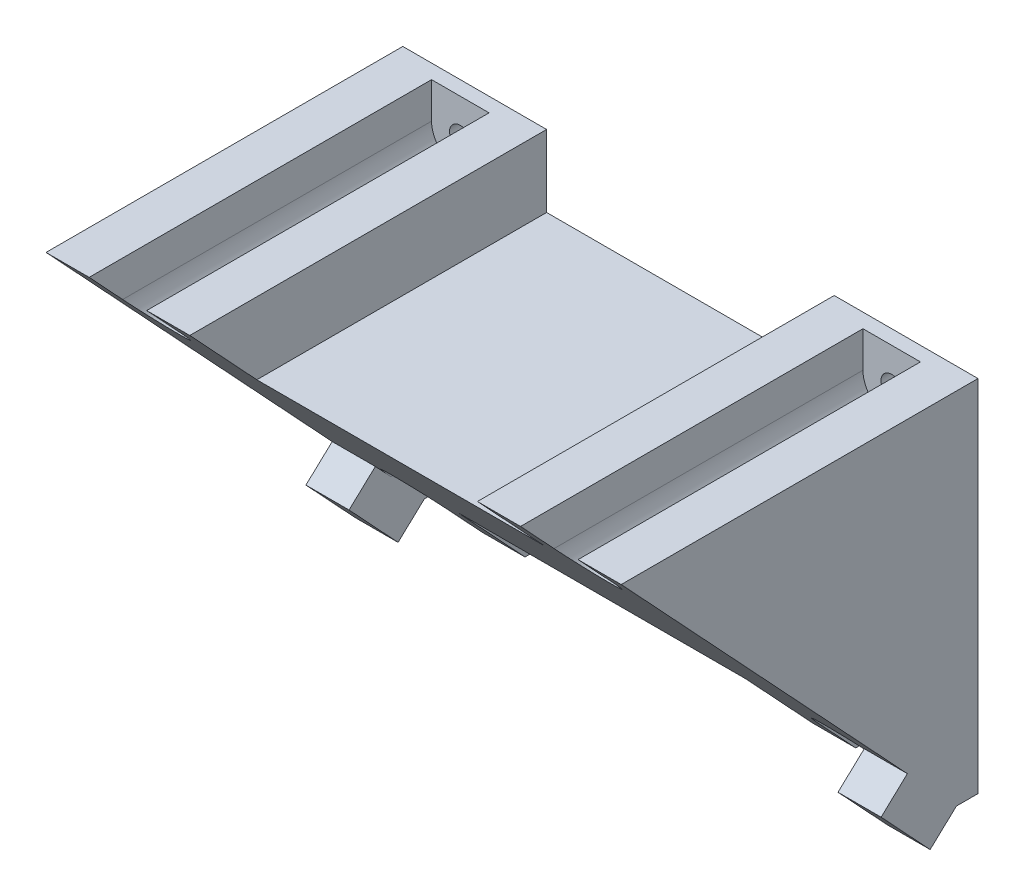
SolidWorks part; units mm, degrees
ref_plane "前视基准面" through (0, 0, 0) normal (0, 0, 1) x (1, 0, 0)
ref_plane "上视基准面" through (0, 0, 0) normal (0, 1, 0) x (1, 0, 0)
ref_plane "右视基准面" through (0, 0, 0) normal (1, 0, 0) x (0, 0, -1)
sketch "草图1" plane through (0, 0, 0) normal (0, 0, 1) x (1, 0, 0)
  line L0 (0, 0) -> (0, 50)
  line L1 (20, 50) -> (20, 40)
  line L2 (60, 40) -> (20, 40)
  line L3 (60, 50) -> (60, 40)
  line L4 (20, 50) -> (0, 50)
  line L5 (60, 50) -> (80, 50)
  line L6 (80, 50) -> (80, 0)
  line L7 (80, 0) -> (60, 0)
  line L8 (60, 0) -> (60, 10)
  line L9 (60, 10) -> (20, 10)
  line L10 (20, 10) -> (20, 0)
  line L11 (20, 0) -> (0, 0)
  point P13 (0, 0)
  point P14 (0, 0)
  dimension "D1" = 50
  dimension "D2" = 20
  dimension "D3" = 40
  dimension "D4" = 20
  dimension "D5" = 20
  dimension "D6" = 40
  dimension "D7" = 20
  dimension "D8" = 10
  dimension "D10" = 10
extrude "凸台-拉伸2" add sketch "草图1" along normal blind 2
sketch "草图3" plane through (0, 0, 2) normal (0, 0, 1) x (1, 0, 0)
  line L0 (10, 5) -> (10, 0) construction
  line L2 (20, 0) -> (0, 0) construction
  line L3 (10, 50) -> (10, 45) construction
  line L4 (20, 50) -> (0, 50) construction
  line L5 (70, 50) -> (70, 45) construction
  line L6 (60, 50) -> (80, 50) construction
  line L7 (70, 0) -> (70, 5) construction
  line L8 (80, 0) -> (60, 0) construction
  circle A1 centre (10, 45) radius 1.5
  circle A2 centre (10, 5) radius 1.5
  circle A3 centre (70, 45) radius 1.5
  circle A4 centre (70, 5) radius 1.5
  point P20 (0, 0)
  dimension "D1" = 3
  dimension "D4" = 3
  dimension "D5" = 3
  dimension "D6" = 3
  dimension "D2" = 40
  dimension "D3" = 40
  dimension "D7" = 60
  dimension "D8" = 60
  dimension "D9" = 10
  dimension "D10" = 10
  dimension "D11" = 10
  dimension "D12" = 10
extrude "切除-拉伸1" cut sketch "草图3" against normal through all
sketch "草图5" plane through (0, 0, 2) normal (0, 0, 1) x (1, 0, 0)
  line L0 (0, 50) -> (6, 50)
  line L1 (20, 50) -> (0, 50) construction
  line L2 (6, 50) -> (6, 45)
  line L3 (14, 45) -> (14, 50)
  line L4 (14, 50) -> (20, 50)
  line L5 (20, 50) -> (20, 40)
  line L6 (20, 40) -> (60, 40)
  line L7 (60, 40) -> (60, 50)
  line L8 (60, 50) -> (66, 50)
  line L9 (60, 50) -> (80, 50) construction
  line L10 (66, 50) -> (66, 45)
  line L11 (74, 45) -> (74, 50)
  line L12 (74, 50) -> (80, 50)
  line L13 (80, 50) -> (80, 0)
  line L14 (80, 0) -> (74, 0)
  line L15 (80, 0) -> (60, 0) construction
  line L16 (74, 0) -> (74, 5)
  line L17 (66, 5) -> (66, 0)
  line L18 (66, 0) -> (60, 0)
  line L19 (60, 0) -> (60, 10)
  line L20 (60, 10) -> (20, 10)
  line L21 (20, 10) -> (20, 0)
  line L22 (20, 0) -> (14, 0)
  line L23 (20, 0) -> (0, 0) construction
  line L24 (14, 0) -> (14, 5)
  line L25 (6, 5) -> (6, 0)
  line L26 (6, 0) -> (0, 0)
  line L27 (0, 0) -> (0, 50)
  arc A0 (6, 45) -> (14, 45) centre (10, 45) ccw
  arc A1 (66, 45) -> (74, 45) centre (70, 45) ccw
  arc A2 (74, 5) -> (66, 5) centre (70, 5) ccw
  arc A3 (14, 5) -> (6, 5) centre (10, 5) ccw
  dimension "D5" = 4
  dimension "D6" = 4
  dimension "D7" = 4
  dimension "D8" = 4
  dimension "D1" = 5
  dimension "D2" = 5
  dimension "D3" = 5
  dimension "D4" = 5
  dimension "D9" = 10
  dimension "D10" = 10
  dimension "D11" = 10
  dimension "D12" = 10
extrude "凸台-拉伸3" add sketch "草图5" along normal blind 1
draft "拔模4" type of draft neutral plane draft angle 43 faces to draft 1 face at (40, 25, 3) neutral plane through (20, 0, 2) neutral plane normal (0, -1, 0) parameters "D1"=43
sketch "草图6" plane through (0, -1.4963, 1.6046) normal (0, -0.682, 0.7314) x (1, 0, 0)
  line L0 (6, 2.046) -> (6, 12.046)
  line L1 (6, 2.046) -> (6, 8.8826) construction
  line L2 (6, 12.046) -> (0, 12.046)
  line L3 (0, 70.4124) -> (0, 2.046) construction
  line L4 (0, 12.046) -> (0, 2.046)
  line L5 (0, 2.046) -> (6, 2.046)
  dimension "D1" = 10
  dimension "D2" = 6
extrude "凸台-拉伸4" add sketch "草图6" along normal blind 5
sketch "草图7" plane through (0, -1.4963, 1.6046) normal (0, -0.682, 0.7314) x (1, 0, 0)
  line L0 (74, 2.046) -> (80, 2.046)
  line L1 (80, 2.046) -> (80, 12.046)
  line L2 (80, 2.046) -> (80, 70.4124) construction
  line L3 (80, 12.046) -> (74, 12.046)
  line L4 (74, 12.046) -> (74, 2.046)
  dimension "D1" = 10
  dimension "D2" = 6
extrude "凸台-拉伸5" add sketch "草图7" along normal blind 5 contours L4 L0 L1 L3
